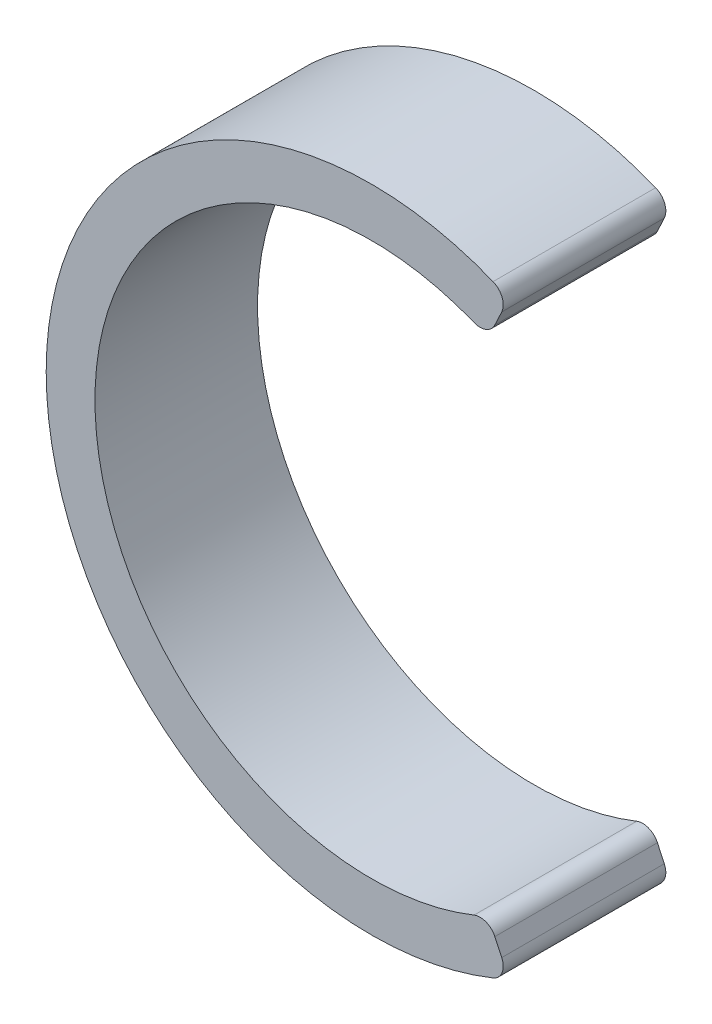
SolidWorks part; units mm, degrees
ref_plane "Front Plane" through (0, 0, 0) normal (0, 0, 1) x (1, 0, 0)
ref_plane "Top Plane" through (0, 0, 0) normal (0, 1, 0) x (1, 0, 0)
ref_plane "Right Plane" through (0, 0, 0) normal (1, 0, 0) x (0, 0, -1)
sketch "Sketch1" plane through (0, 0, 0) normal (0, 0, 1) x (1, 0, 0)
  line L0 (7.5954, 16.2883) -> (8.0186, 17.196)
  line L1 (7.5954, -16.2883) -> (8.0186, -17.196)
  line L2 (0, -1000) -> (0, 49000) construction
  line L5 (0, 0) -> (7.1845, 15.4072) construction
  line L6 (0, 0) -> (7.1845, -15.4072) construction
  line L7 (3.3101, 0) -> (11.0757, 16.6532) construction
  line L8 (3.3101, 0) -> (11.0757, -16.6532) construction
  arc A0 (6.3175, 15.7826) -> (6.3175, -15.7826) centre (0, 0) ccw
  arc A1 (7.4866, 18.5459) -> (7.4866, -18.5459) centre (0, 0) ccw
  arc A2 (8.0186, 17.196) -> (7.4866, 18.5459) centre (7.1123, 17.6186) ccw
  arc A3 (11.0757, 16.6532) -> (11.0757, -16.6532) centre (0, 0) ccw construction
  arc A4 (7.1845, 15.4072) -> (7.1845, -15.4072) centre (0, 0) ccw construction
  arc A5 (7.5954, 16.2883) -> (6.3175, 15.7826) centre (6.6891, 16.711) cw
  arc A6 (7.5954, -16.2883) -> (6.3175, -15.7826) centre (6.6891, -16.711) ccw
  arc A7 (8.0186, -17.196) -> (7.4866, -18.5459) centre (7.1123, -17.6186) cw
  dimension "D1" = 34
  dimension "D5" = 1
  dimension "D6" = 1
  dimension "D7" = 1
  dimension "D8" = 1
  dimension "D2" = 25
  dimension "D3" = 25
  dimension "D4" = 3
extrude "Boss-Extrude1" add sketch "Sketch1" along normal blind 10
